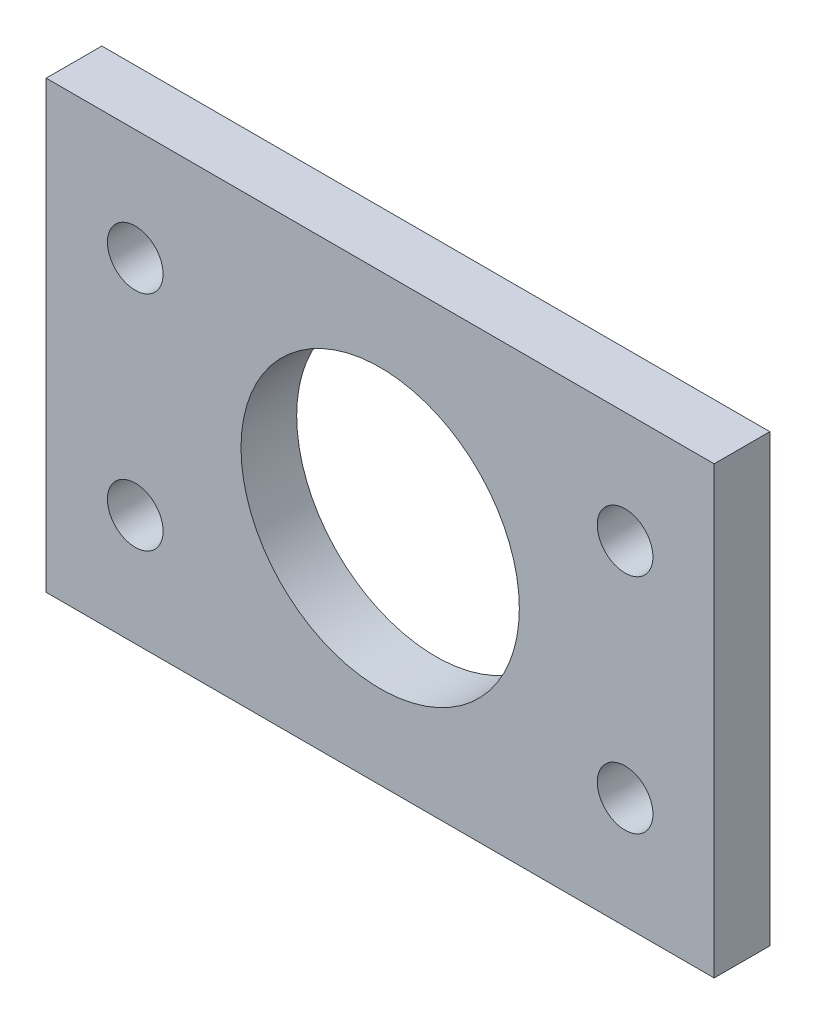
SolidWorks part; units mm, degrees
ref_plane "Front Plane" through (0, 0, 0) normal (0, 0, 1) x (1, 0, 0)
ref_plane "Top Plane" through (0, 0, 0) normal (0, 1, 0) x (1, 0, 0)
ref_plane "Right Plane" through (0, 0, 0) normal (1, 0, 0) x (0, 0, -1)
sketch "Sketch1" plane through (0, 0, 0) normal (0, 0, 1) x (1, 0, 0)
  line L1 (0, 0) -> (60, 0)
  line L2 (0, 0) -> (0, 40)
  line L3 (0, 40) -> (60, 40)
  line L4 (60, 0) -> (60, 40)
  dimension "D1" = 40
  dimension "D2" = 60
extrude "Boss-Extrude1" add sketch "Sketch1" along normal blind 5
sketch "Sketch2" plane through (0, 0, 5) normal (0, 0, 1) x (1, 0, 0)
  line L0 (60, 40) -> (0, 40) construction
  line L1 (0, 40) -> (0, 0) construction
  circle A0 centre (30, 20) radius 12.5
  dimension "D1" = 25
  dimension "D2" = 20
  dimension "D3" = 30
extrude "Cut-Extrude1" cut sketch "Sketch2" against normal blind 5
sketch "Sketch3" plane through (0, 0, 5) normal (0, 0, 1) x (1, 0, 0)
  line L0 (60, 40) -> (0, 40) construction
  line L1 (0, 40) -> (0, 0) construction
  line L2 (60, 0) -> (60, 40) construction
  line L3 (0, 0) -> (60, 0) construction
  circle A0 centre (8, 30) radius 2.5
  circle A1 centre (8, 10) radius 2.5
  circle A2 centre (52, 10) radius 2.5
  circle A3 centre (52, 30) radius 2.5
  dimension "D1" = 5
  dimension "D2" = 5
  dimension "D3" = 5
  dimension "D4" = 5
  dimension "D5" = 10
  dimension "D6" = 8
  dimension "D7" = 10
  dimension "D8" = 8
  dimension "D9" = 8
  dimension "D10" = 10
  dimension "D11" = 10
  dimension "D12" = 8
extrude "Cut-Extrude2" cut sketch "Sketch3" against normal blind 10
